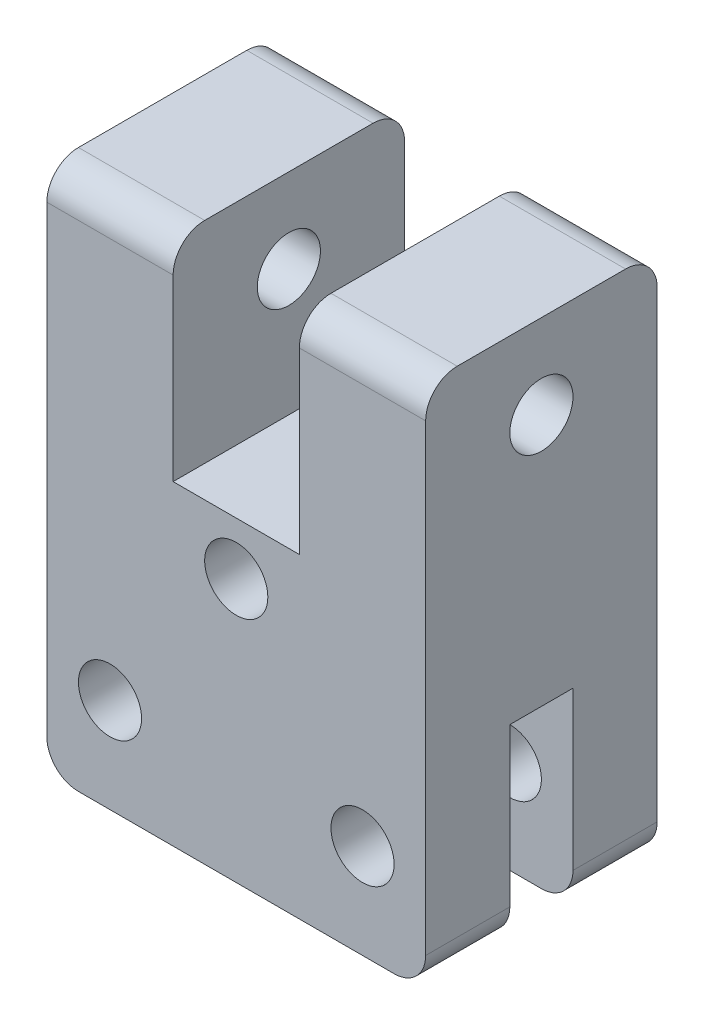
SolidWorks part; units mm, degrees
ref_plane "Alzado" through (0, 0, 0) normal (0, 0, 1) x (1, 0, 0)
ref_plane "Planta" through (0, 0, 0) normal (0, 1, 0) x (1, 0, 0)
ref_plane "Vista lateral" through (0, 0, 0) normal (1, 0, 0) x (0, 0, -1)
sketch "Croquis2" plane through (0, 0, 0) normal (0, 0, 1) x (1, 0, 0)
  line L1 (-9, 7.5) -> (9, 7.5)
  line L2 (-9, 7.5) -> (-9, -7.5)
  line L3 (-9, -7.5) -> (9, -7.5)
  line L4 (9, 7.5) -> (9, -7.5)
  point P4 (0, -7.5)
  point P6 (9, 0)
  dimension "D1" = 18
  dimension "D2" = 15
extrude "Saliente-Extruir1" add sketch "Croquis2" along normal mid plane 11
sketch "Croquis3" plane through (0, 0, 0) normal (0, 0, 1) x (1, 0, 0)
  line L0 (-9, 7.5) -> (-9, -7.5) construction
  line L1 (-9, 1.5) -> (9, 1.5)
  line L2 (-9, 1.5) -> (-9, -7.5)
  line L3 (-9, -7.5) -> (9, -7.5)
  line L4 (9, 1.5) -> (9, -7.5)
  dimension "D1" = 9
extrude "Cortar-Extruir1" cut sketch "Croquis3" against normal mid plane 3
sketch "Croquis4" plane through (0, 0, 0) normal (0, 0, 1) x (1, 0, 0)
  line L0 (0.5, -1.5) -> (-0.5, -1.5)
  line L1 (-1.5, -3) -> (-1.5, -7.5)
  line L2 (-9, -7.5) -> (9, -7.5) construction
  line L3 (1.5, -3) -> (1.5, -7.5)
  line L4 (-1.5, -7.5) -> (1.5, -7.5)
  line L5 (9, 1.5) -> (-9, 1.5) construction
  line L6 (1.5, -2.5) -> (1.5, -3)
  line L7 (-1.5, -2.5) -> (-1.5, -3)
  arc A0 (1.5, -3) -> (-1.5, -3) centre (0, -3) ccw construction
  arc A1 (-0.5, -1.5) -> (-1.5, -2.5) centre (-0.5, -2.5) ccw
  arc A2 (0.5, -1.5) -> (1.5, -2.5) centre (0.5, -2.5) cw
  point P4 (0, -1.5)
  point P14 (0, -1.5)
  point P16 (-1.5, -1.5)
  point P19 (1.5, -1.5)
  dimension "D2" = 3
  dimension "D4" = 1
  dimension "D1" = 3
  dimension "D3" = 3
extrude "Cortar-Extruir2" cut sketch "Croquis4" against normal through all
sketch "Croquis10" plane through (0, 7.5, 0) normal (0, 1, 0) x (1, 0, 0)
  line L0 (-3, 5.5) -> (-3, -5.5)
  line L1 (3, 5.5) -> (3, -5.5)
  line L2 (0, 5.5) -> (0, -5.5) construction
  line L3 (-3, 5.5) -> (-9, 5.5)
  line L4 (9, 5.5) -> (-9, 5.5)
  line L5 (-9, 5.5) -> (-9, -5.5)
  line L6 (-9, -5.5) -> (9, -5.5)
  line L7 (9, -5.5) -> (9, 5.5)
  line L8 (9, 5.5) -> (3, 5.5)
  line L9 (-9, 5.5) -> (-9, -5.5)
  line L10 (-9, -5.5) -> (-3, -5.5)
  line L11 (9, -5.5) -> (9, 5.5)
  line L12 (3, -5.5) -> (9, -5.5)
  line L13 (9, 5.5) -> (-9, 5.5) construction
  point P11 (0, 0)
  dimension "D2" = 6
  dimension "D1" = 0
extrude "Saliente-Extruir4" add sketch "Croquis10" along normal blind 10
sketch "Croquis7" plane through (0, 0, 0) normal (1, 0, 0) x (0, 0, -1)
  line L1 (-5.5, 17.5) -> (5.5, 17.5) construction
  circle A0 centre (0, 13.5) radius 1.5
  dimension "D1" = 3
  dimension "D2" = 4
extrude "Cortar-Extruir3" cut sketch "Croquis7" against normal through all both and the other way through all
sketch "Croquis11" plane through (0, 0, 0) normal (0, 0, 1) x (1, 0, 0)
  line L0 (6, 17.5) -> (6, -7.5) construction
  line L1 (9, 17.5) -> (3, 17.5) construction
  line L2 (1.5, -7.5) -> (9, -7.5) construction
  line L3 (-6, 17.5) -> (-6, -7.5) construction
  line L4 (-3, 17.5) -> (-9, 17.5) construction
  line L5 (-9, -7.5) -> (-1.5, -7.5) construction
  line L6 (6, -3) -> (-6, -3) construction
  circle A0 centre (6, -3) radius 1.5
  circle A1 centre (-6, -3) radius 1.5
  dimension "D2" = 3
  dimension "D1" = 4.5
extrude "Cortar-Extruir4" cut sketch "Croquis11" against normal through all both and the other way through all
fillet "Redondeo2" radius 1.5 4 edges at (-6, 17.5, 5.5) (6, 17.5, 5.5) (-6, 17.5, -5.5) (6, 17.5, -5.5)
fillet "Redondeo3" radius 1.5 4 edges at (-9, -7.5, -3.5) (-9, -7.5, 3.5) (9, -7.5, -3.5) (9, -7.5, 3.5)
sketch "Croquis15" plane through (0, 0, 5.5) normal (0, 0, 1) x (1, 0, 0)
  circle A0 centre (0, 5) radius 1.5
  dimension "D2" = 3
  dimension "D1" = 5
extrude "Cortar-Extruir7" cut sketch "Croquis15" against normal blind 10
